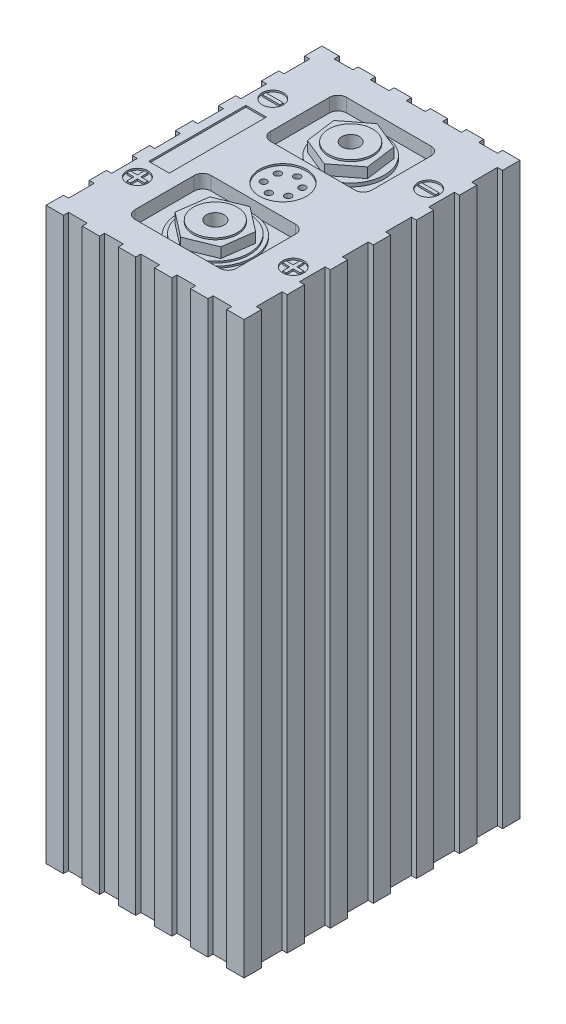
SolidWorks part; units mm, degrees
ref_plane "Спереди" through (0, 0, 0) normal (0, 0, 1) x (1, 0, 0)
ref_plane "Сверху" through (0, 0, 0) normal (0, 1, 0) x (1, 0, 0)
ref_plane "Справа" through (0, 0, 0) normal (1, 0, 0) x (0, 0, -1)
sketch "Эскиз1" plane through (0, 0, 0) normal (0, 1, 0) x (1, 0, 0)
  line L0 (-63.5363, 0) -> (0, 0) construction
  line L1 (0, -79.6623) -> (0, 79.6623) construction
  line L2 (5.5524, 78.5) -> (-5.5524, 78.5)
  line L3 (-5.5524, 78.5) -> (-5.5524, 81.5)
  line L4 (-5.5524, 81.5) -> (-15.7984, 81.5)
  line L5 (-15.7984, 81.5) -> (-15.7984, 78.5)
  line L6 (-15.7984, 78.5) -> (-26.9032, 78.5)
  line L7 (-26.9032, 78.5) -> (-26.9032, 81.5)
  line L8 (-26.9032, 81.5) -> (-37.1492, 81.5)
  line L9 (-37.1492, 81.5) -> (-37.1492, 78.5)
  line L10 (-37.1492, 78.5) -> (-48.254, 78.5)
  line L11 (-48.254, 78.5) -> (-48.254, 81.5)
  line L12 (-48.254, 81.5) -> (-58.5, 81.5)
  line L13 (-58.5, 81.5) -> (-58.5, 71.254)
  line L14 (-58.5, 71.254) -> (-55.5, 71.254)
  line L15 (-55.5, 71.254) -> (-55.5, 56.041)
  line L16 (-55.5, 56.041) -> (-58.5, 56.041)
  line L17 (-58.5, 56.041) -> (-58.5, 45.795)
  line L18 (-58.5, 45.795) -> (-55.5, 45.795)
  line L19 (-55.5, 45.795) -> (-55.5, 30.582)
  line L20 (-55.5, 30.582) -> (-58.5, 30.582)
  line L21 (-58.5, 30.582) -> (-58.5, 20.336)
  line L22 (-58.5, 20.336) -> (-55.5, 20.336)
  line L23 (-55.5, 20.336) -> (-55.5, 5.123)
  line L24 (-55.5, 5.123) -> (-58.5, 5.123)
  line L25 (-58.5, 5.123) -> (-58.5, -5.123)
  line L28 (58.5, 30.582) -> (58.5, 25.2147) construction
  line L29 (22.5319, 78.5) -> (15.7984, 78.5) construction
  line L30 (58.5, 5.123) -> (58.5, -5.123)
  line L31 (55.5, 5.123) -> (58.5, 5.123)
  line L32 (55.5, 20.336) -> (55.5, 5.123)
  line L33 (58.5, 20.336) -> (55.5, 20.336)
  line L34 (58.5, 30.582) -> (58.5, 20.336)
  line L35 (55.5, 30.582) -> (58.5, 30.582)
  line L36 (55.5, 45.795) -> (55.5, 30.582)
  line L37 (58.5, 45.795) -> (55.5, 45.795)
  line L38 (58.5, 56.041) -> (58.5, 45.795)
  line L39 (55.5, 56.041) -> (58.5, 56.041)
  line L40 (55.5, 71.254) -> (55.5, 56.041)
  line L41 (58.5, 71.254) -> (55.5, 71.254)
  line L42 (58.5, 81.5) -> (58.5, 71.254)
  line L43 (48.254, 81.5) -> (58.5, 81.5)
  line L44 (48.254, 78.5) -> (48.254, 81.5)
  line L45 (37.1492, 78.5) -> (48.254, 78.5)
  line L46 (37.1492, 81.5) -> (37.1492, 78.5)
  line L47 (26.9032, 81.5) -> (37.1492, 81.5)
  line L48 (26.9032, 78.5) -> (26.9032, 81.5)
  line L49 (15.7984, 78.5) -> (26.9032, 78.5)
  line L50 (15.7984, 81.5) -> (15.7984, 78.5)
  line L51 (5.5524, 81.5) -> (15.7984, 81.5)
  line L52 (5.5524, 78.5) -> (5.5524, 81.5)
  line L53 (22.5319, -78.5) -> (15.7984, -78.5) construction
  line L54 (58.5, -30.582) -> (58.5, -25.2147) construction
  line L55 (-58.5, -30.582) -> (-58.5, -25.2147) construction
  line L56 (-22.5319, -78.5) -> (-15.7984, -78.5) construction
  line L57 (5.5524, -78.5) -> (5.5524, -81.5)
  line L58 (5.5524, -81.5) -> (15.7984, -81.5)
  line L59 (15.7984, -81.5) -> (15.7984, -78.5)
  line L60 (15.7984, -78.5) -> (26.9032, -78.5)
  line L61 (26.9032, -78.5) -> (26.9032, -81.5)
  line L62 (26.9032, -81.5) -> (37.1492, -81.5)
  line L63 (37.1492, -81.5) -> (37.1492, -78.5)
  line L64 (37.1492, -78.5) -> (48.254, -78.5)
  line L65 (48.254, -78.5) -> (48.254, -81.5)
  line L66 (48.254, -81.5) -> (58.5, -81.5)
  line L67 (58.5, -81.5) -> (58.5, -71.254)
  line L68 (58.5, -71.254) -> (55.5, -71.254)
  line L69 (55.5, -71.254) -> (55.5, -56.041)
  line L70 (55.5, -56.041) -> (58.5, -56.041)
  line L71 (58.5, -56.041) -> (58.5, -45.795)
  line L72 (58.5, -45.795) -> (55.5, -45.795)
  line L73 (55.5, -45.795) -> (55.5, -30.582)
  line L74 (55.5, -30.582) -> (58.5, -30.582)
  line L75 (58.5, -30.582) -> (58.5, -20.336)
  line L76 (58.5, -20.336) -> (55.5, -20.336)
  line L77 (55.5, -20.336) -> (55.5, -5.123)
  line L78 (55.5, -5.123) -> (58.5, -5.123)
  line L79 (-55.5, -5.123) -> (-58.5, -5.123)
  line L80 (-55.5, -20.336) -> (-55.5, -5.123)
  line L81 (-58.5, -20.336) -> (-55.5, -20.336)
  line L82 (-58.5, -30.582) -> (-58.5, -20.336)
  line L83 (-55.5, -30.582) -> (-58.5, -30.582)
  line L84 (-55.5, -45.795) -> (-55.5, -30.582)
  line L85 (-58.5, -45.795) -> (-55.5, -45.795)
  line L86 (-58.5, -56.041) -> (-58.5, -45.795)
  line L87 (-55.5, -56.041) -> (-58.5, -56.041)
  line L88 (-55.5, -71.254) -> (-55.5, -56.041)
  line L89 (-58.5, -71.254) -> (-55.5, -71.254)
  line L90 (-58.5, -81.5) -> (-58.5, -71.254)
  line L91 (-48.254, -81.5) -> (-58.5, -81.5)
  line L92 (-48.254, -78.5) -> (-48.254, -81.5)
  line L93 (-37.1492, -78.5) -> (-48.254, -78.5)
  line L94 (-37.1492, -81.5) -> (-37.1492, -78.5)
  line L95 (-26.9032, -81.5) -> (-37.1492, -81.5)
  line L96 (-26.9032, -78.5) -> (-26.9032, -81.5)
  line L97 (-15.7984, -78.5) -> (-26.9032, -78.5)
  line L98 (-15.7984, -81.5) -> (-15.7984, -78.5)
  line L99 (-5.5524, -81.5) -> (-15.7984, -81.5)
  line L100 (-5.5524, -78.5) -> (-5.5524, -81.5)
  line L101 (5.5524, -78.5) -> (-5.5524, -78.5)
  point P59 (0, 78.5)
  point P89 (58.5, 0)
  point P90 (-58.5, 0)
  point P110 (0, -78.5)
  dimension "D1" = 163
  dimension "D2" = 117
  dimension "D3" = 3
extrude "Бобышка-Вытянуть1" add sketch "Эскиз1" along normal blind 337
sketch "Эскиз2" plane through (0, 337, 0) normal (0, 1, 0) x (1, 0, 0)
  line L0 (0, 0) -> (75.2051, 0) construction
  line L1 (-25, -62.5) -> (25, -62.5)
  line L2 (-30, -57.5) -> (-30, -22.5)
  line L3 (-25, -17.5) -> (25, -17.5)
  line L4 (30, -57.5) -> (30, -22.5)
  line L5 (-30, -62.5) -> (30, -17.5) construction
  line L6 (-30, -17.5) -> (30, -62.5) construction
  line L7 (-30, 17.5) -> (30, 62.5) construction
  line L8 (-30, 62.5) -> (30, 17.5) construction
  line L9 (30, 57.5) -> (30, 22.5)
  line L10 (-25, 17.5) -> (25, 17.5)
  line L11 (-30, 57.5) -> (-30, 22.5)
  line L12 (-25, 62.5) -> (25, 62.5)
  arc A0 (25, -62.5) -> (30, -57.5) centre (25, -57.5) ccw
  arc A1 (25, -17.5) -> (30, -22.5) centre (25, -22.5) cw
  arc A2 (-30, -22.5) -> (-25, -17.5) centre (-25, -22.5) cw
  arc A3 (-25, -62.5) -> (-30, -57.5) centre (-25, -57.5) cw
  circle A4 centre (0, -40) radius 20
  circle A5 centre (0, 40) radius 20
  arc A6 (-25, 62.5) -> (-30, 57.5) centre (-25, 57.5) ccw
  arc A7 (-30, 22.5) -> (-25, 17.5) centre (-25, 22.5) ccw
  arc A8 (25, 17.5) -> (30, 22.5) centre (25, 22.5) ccw
  arc A9 (25, 62.5) -> (30, 57.5) centre (25, 57.5) cw
  circle A10 centre (0, -8.3803) radius 1.9621
  circle A11 centre (-7.2576, -4.1902) radius 1.9621
  circle A12 centre (-7.2576, 4.1902) radius 1.9621
  circle A13 centre (0, 8.3803) radius 1.9621
  circle A14 centre (7.2576, 4.1902) radius 1.9621
  circle A15 centre (7.2576, -4.1902) radius 1.9621
  point P0 (0, -40)
  point P55 (0, 0)
  dimension "D4" = 5
  dimension "D5" = 40
  dimension "D1" = 40
  dimension "D2" = 60
  dimension "D3" = 45
  dimension "D6" = 6
extrude "Вырез-Вытянуть1" cut sketch "Эскиз2" against normal blind 8
sketch "Эскиз4" plane through (0, 337, 0) normal (0, 1, 0) x (1, 0, 0)
  line L0 (0, 0) -> (72.1577, 0) construction
  line L1 (-16.8694, -46.908) -> (-2.4523, -58.0633)
  line L2 (-2.4523, -58.0633) -> (14.4172, -51.1554)
  line L3 (14.4172, -51.1554) -> (16.8694, -33.092)
  line L4 (16.8694, -33.092) -> (2.4523, -21.9367)
  line L5 (2.4523, -21.9367) -> (-14.4172, -28.8446)
  line L6 (-14.4172, -28.8446) -> (-16.8694, -46.908)
  line L7 (-14.4172, 28.8446) -> (-16.8694, 46.908)
  line L8 (2.4523, 21.9367) -> (-14.4172, 28.8446)
  line L9 (16.8694, 33.092) -> (2.4523, 21.9367)
  line L10 (14.4172, 51.1554) -> (16.8694, 33.092)
  line L11 (-2.4523, 58.0633) -> (14.4172, 51.1554)
  line L12 (-16.8694, 46.908) -> (-2.4523, 58.0633)
  circle A0 centre (0, -40) radius 20
  circle A1 centre (0, -40) radius 15.7868 construction
  circle A2 centre (0, 40) radius 15.7868 construction
  circle A3 centre (0, 40) radius 20
extrude "Вырез-Вытянуть2" cut sketch "Эскиз4" against normal blind 6
sketch "Эскиз5" plane through (0, 337, 0) normal (0, 1, 0) x (1, 0, 0)
  circle A0 centre (0, 40) radius 13
  circle A1 centre (0, -40) radius 13
  dimension "D1" = 26
extrude "Бобышка-Вытянуть2" add sketch "Эскиз5" along normal blind 1
sketch "Эскиз6" plane through (0, 338, 0) normal (0, 1, 0) x (1, 0, 0)
  point P0 (0, 40)
  point P1 (0, -40)
hole_wizard "Отверстие обработанное метчиком M12x1.251" positions "Эскиз7" profile "Эскиз8" tap size "M12x1.25" standard "GB"
sketch "Эскиз7" plane through (0, 338, 0) normal (0, 1, 0) x (1, 0, 0)
  point P0 (0, 40)
  point P3 (0, -40)
sketch "Эскиз8" plane through (0, 338, -40) normal (1, 0, 0) x (0, 0, 1)
  line L0 (0, 0) -> (0, 33.4045)
  line L1 (0, 33.4045) -> (5.25, 30.25)
  line L2 (5.25, 30.25) -> (5.25, 0)
  line L5 (5.25, 0) -> (0, 0)
  line L10 (0, 33.4045) -> (-5.25, 30.25) construction
  line L11 (0, -6.35) -> (0, 107.95) construction
  dimension "Диаметр сверла" = 10.5
  dimension "Глубина сверла" = 30.25
  dimension "Угол заточки сверла" = 118
cosmetic thread "Отверстие резьбы1"
cosmetic thread "Отверстие резьбы2"
sketch "Эскиз9" plane through (0, 337, 0) normal (0, 1, 0) x (1, 0, 0)
  line L0 (0, 0) -> (74.3344, 0) construction
  line L1 (-50.6083, -28.6992) -> (-38.5239, -28.6992)
  line L2 (-50.6083, -28.6992) -> (-50.6083, 28.6992)
  line L3 (-50.6083, 28.6992) -> (-38.5239, 28.6992)
  line L4 (-38.5239, -28.6992) -> (-38.5239, 28.6992)
  line L5 (-50.6083, -28.6992) -> (-38.5239, 28.6992) construction
  line L6 (-50.6083, 28.6992) -> (-38.5239, -28.6992) construction
  line L7 (0, 0) -> (0, 31.018) construction
  line L8 (-51.2469, -41.0202) -> (-40.8276, -38.9798) construction
  line L9 (-51.2469, 38.9798) -> (-40.8276, 38.9798)
  line L10 (-51.2469, 38.9798) -> (-51.2469, 41.0202)
  line L11 (-51.2469, 41.0202) -> (-40.8276, 41.0202)
  line L12 (-40.8276, 38.9798) -> (-40.8276, 41.0202)
  line L13 (-51.2469, 38.9798) -> (-40.8276, 41.0202) construction
  line L14 (-51.2469, 41.0202) -> (-40.8276, 38.9798) construction
  line L15 (-51.2469, -38.9798) -> (-40.8276, -41.0202) construction
  line L16 (-40.8276, -38.9798) -> (-40.8276, -41.0202)
  line L17 (-51.2469, -41.0202) -> (-40.8276, -41.0202)
  line L18 (-51.2469, -38.9798) -> (-51.2469, -41.0202)
  line L19 (-51.2469, -38.9798) -> (-40.8276, -38.9798)
  line L20 (-45.0171, -45.2096) -> (-47.0574, -45.2096)
  line L21 (-47.0574, -34.7904) -> (-47.0574, -45.2096)
  line L22 (-45.0171, -34.7904) -> (-47.0574, -34.7904)
  line L23 (-45.0171, -34.7904) -> (-45.0171, -45.2096)
  line L24 (-46.0373, -40) -> (-40.8276, -41.0202) construction
  line L25 (-46.0373, -40) -> (-47.0574, -45.2096) construction
  line L26 (46.0373, -40) -> (47.0574, -45.2096) construction
  line L27 (46.0373, -40) -> (40.8276, -41.0202) construction
  line L28 (51.2469, -38.9798) -> (40.8276, -41.0202) construction
  line L29 (51.2469, 41.0202) -> (40.8276, 38.9798) construction
  line L30 (51.2469, 38.9798) -> (40.8276, 41.0202) construction
  line L31 (51.2469, -41.0202) -> (40.8276, -38.9798) construction
  line L32 (45.0171, -34.7904) -> (45.0171, -45.2096)
  line L33 (45.0171, -34.7904) -> (47.0574, -34.7904)
  line L34 (47.0574, -34.7904) -> (47.0574, -45.2096)
  line L35 (45.0171, -45.2096) -> (47.0574, -45.2096)
  line L36 (51.2469, -38.9798) -> (40.8276, -38.9798)
  line L37 (51.2469, -38.9798) -> (51.2469, -41.0202)
  line L38 (51.2469, -41.0202) -> (40.8276, -41.0202)
  line L39 (40.8276, -38.9798) -> (40.8276, -41.0202)
  line L40 (40.8276, 38.9798) -> (40.8276, 41.0202)
  line L41 (51.2469, 41.0202) -> (40.8276, 41.0202)
  line L42 (51.2469, 38.9798) -> (51.2469, 41.0202)
  line L43 (51.2469, 38.9798) -> (40.8276, 38.9798)
  circle A0 centre (-46.0373, 40) radius 6.2496
  circle A1 centre (-46.0373, -40) radius 6.2496
  circle A2 centre (46.0373, -40) radius 6.2496
  circle A3 centre (46.0373, 40) radius 6.2496
  point P0 (-44.5661, 0)
  dimension "D2" = 90
  dimension "D1" = 2
extrude "Вырез-Вытянуть3" cut sketch "Эскиз9" against normal blind 1 contours A0 L12 L9 L10 L11 | L1 L4 L3 L2 | A1 L22 L23 L19 L16 L17 L20 L21 L18 | A2 L39 L36 L32 L33 L34 L37 L38 L35 | A3 L42 L43 L40 L41
sketch "Эскиз10" plane through (0, 329, 0) normal (0, 1, 0) x (1, 0, 0)
  circle A0 centre (0, -40) radius 13
  circle A1 centre (0, -40) radius 22.2574
extrude "Бобышка-Вытянуть3" add sketch "Эскиз10" along normal blind 1
sketch "Эскиз11" plane through (0, 337, 0) normal (0, 1, 0) x (1, 0, 0)
  circle A0 centre (0, 0) radius 13.8601
extrude "Вырез-Вытянуть4" cut sketch "Эскиз11" against normal blind 1
scale "Scale1" bodies to scale 110 scale about centroid uniform scaling yes scale factor 0.5
scale "Scale2" bodies to scale 111 scale about centroid uniform scaling yes scale factor 0.5
